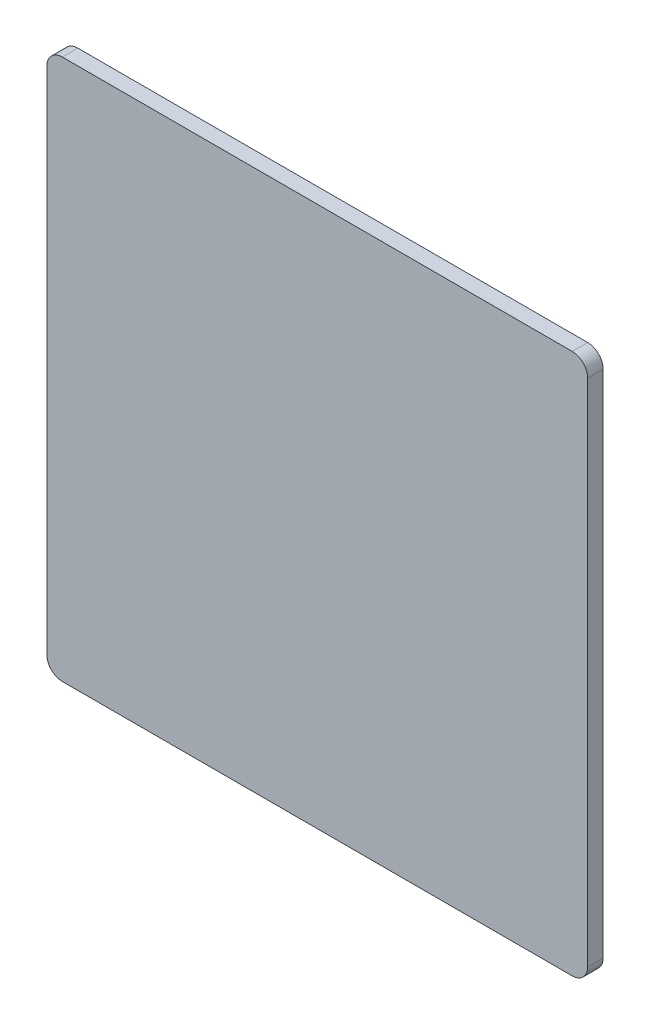
SolidWorks part; units mm, degrees
ref_plane "Plan de face" through (0, 0, 0) normal (0, 0, 1) x (1, 0, 0)
ref_plane "Plan de dessus" through (0, 0, 0) normal (0, 1, 0) x (1, 0, 0)
ref_plane "Plan de droite" through (0, 0, 0) normal (1, 0, 0) x (0, 0, -1)
sketch "Esquisse1" plane through (0, 0, 0) normal (0, 0, 1) x (1, 0, 0)
  line L10 (-35, -35) -> (35, -35)
  line L11 (-35, -35) -> (-35, 35)
  line L12 (-35, 35) -> (35, 35)
  line L13 (35, -35) -> (35, 35)
  line L14 (-35, -35) -> (35, 35) construction
  line L15 (-35, 35) -> (35, -35) construction
  point P0 (0, 0)
  dimension "D1" = 70
  dimension "D2" = 70
extrude "Boss.-Extru.1" add sketch "Esquisse1" along normal blind 2
sketch "Esquisse3" plane through (0, -35, 0) normal (0, -1, 0) x (1, 0, 0)
  line L0 (-35, 2) -> (35, 2) construction
  line L1 (0, -1.1) -> (0, 1.1) construction
  line L2 (7.2, 1.9) -> (-7.2, 1.9)
  line L3 (7.2, 1.9) -> (7.2, -6.5)
  line L4 (7.2, -6.5) -> (-7.2, -6.5)
  line L5 (-7.2, 1.9) -> (-7.2, -6.5)
  line L8 (5.2, -0.1) -> (-5.2, -0.1)
  line L9 (5.2, -0.1) -> (5.2, -4.5)
  line L10 (5.2, -4.5) -> (-5.2, -4.5)
  line L11 (-5.2, -0.1) -> (-5.2, -4.5)
  line L12 (5.2, -0.1) -> (-5.2, -4.5) construction
  line L13 (5.2, -4.5) -> (-5.2, -0.1) construction
  point P0 (0, 1.9)
  point P9 (0, -2.3)
  point P15 (-7.2, -2.3)
  dimension "D1" = 14.4
  dimension "D2" = 8.4
  dimension "D3" = 2
  dimension "D4" = 2
  dimension "D5" = 0.1
extrude "Boss.-Extru.3" add sketch "Esquisse3" against normal blind 15
draft "Dépouille3" type of draft neutral plane draft angle 2 faces to draft 4 face at (0, -27.5, -0.1) face at (-5.2, -27.5, -2.3) face at (0, -27.5, -4.5) face at (5.2, -27.5, -2.3) neutral plane through (-35, -35, 2) neutral plane normal (0, -1, 0) parameters "D1"=2
ref_plane "Plan1" through (0, 0, -2.3) normal (0, 0, 1) x (1, 0, 0)
fillet "Congé1" radius 2 4 edges at (35, -35, 1) (-35, -35, 1) (-35, 35, 1) (35, 35, 1)
